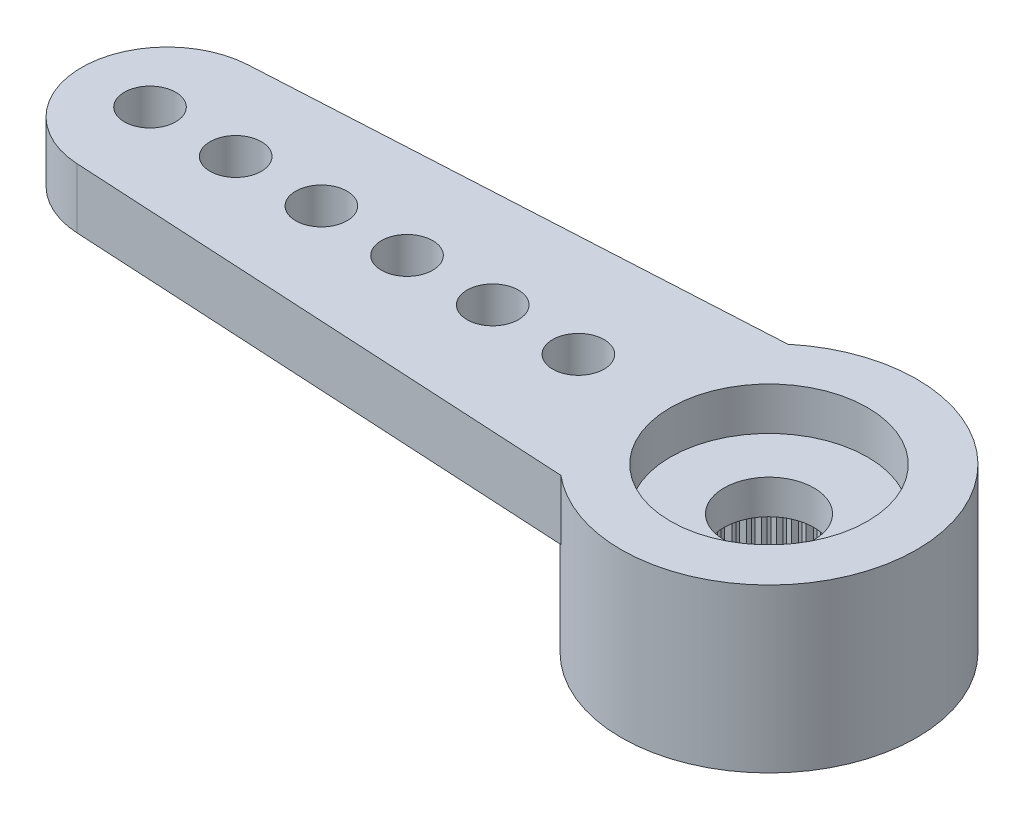
SolidWorks part; units mm, degrees
material "PVC Rígido"
ref_plane "Plano frontal" through (0, 0, 0) normal (0, 0, 1) x (1, 0, 0)
ref_plane "Plano superior" through (0, 0, 0) normal (0, 1, 0) x (1, 0, 0)
ref_plane "Plano direito" through (0, 0, 0) normal (1, 0, 0) x (0, 0, -1)
sketch "Esboço1" plane through (0, 0, 0) normal (0, 1, 0) x (1, 0, 0)
  line L0 (0, 0) -> (-14.05, 0) construction
  line L1 (-14.1591, 1.997) -> (-2.2091, 2.65)
  line L2 (-2.2091, -2.65) -> (-14.1591, -1.997)
  arc A0 (-2.2091, -2.65) -> (-2.2091, 2.65) centre (0, 0) ccw
  arc A1 (-14.1591, 1.997) -> (-14.1591, -1.997) centre (-14.05, 0) ccw
  dimension "D1" = 6.9
  dimension "D2" = 4
  dimension "D3" = 19.5
  dimension "D4" = 5.3
extrude "Ressalto-extrusão1" add sketch "Esboço1" against normal blind 1.4
sketch "Esboço2" plane through (0, -1.4, 0) normal (0, -1, 0) x (1, 0, 0)
  arc A0 (-2.2091, -2.65) -> (-2.2091, 2.65) centre (0, 0) ccw construction
  circle A1 centre (0, 0) radius 3.45
extrude "Ressalto-extrusão2" add sketch "Esboço2" along normal offset from surface (2.4 mm away) 3.8 up to face at (-7.242, 0, 0)
hole_wizard "Furo4" positions "Esboço9" profile "Esboço10" legacy end condition through all
sketch "Esboço9" plane through (0, 0, 0) normal (0, 1, 0) x (1, 0, 0)
  line L1 (-14.45, 0) -> (0, 0) construction
  arc A2 (-14.1591, 1.997) -> (-14.1591, -1.997) centre (-14.05, 0) ccw construction
  point P0 (-14.45, 0)
  point P19 (-16.05, 0)
  dimension "D1" = 1.6
sketch "Esboço10" plane through (-14.45, 0, 0) normal (1, 0, 0) x (0, 0, 1)
  line L0 (0, 0) -> (0, 3.8)
  line L1 (0, 3.8) -> (0.6, 3.8)
  line L2 (0.6, 3.8) -> (0.6, 0)
  line L3 (0.6, 0) -> (0, 0)
  line L4 (0, 110) -> (0, -10) construction
  dimension "Diameter" = 1.2
  dimension "Depth" = 3.8
pattern_linear "Padrão linear1" count 6 spacing 2 along (1, 0, 0) of "Furo4"
hole_wizard "Furo1" positions "Esboço3" profile "Esboço4" legacy
sketch "Esboço3" plane through (0, -3.8, 0) normal (0, -1, 0) x (-1, 0, 0)
  point P0 (0, 0)
sketch "Esboço4" plane through (0, -3.8, 0) normal (1, 0, 0) x (0, 0, -1)
  line L0 (0, 0) -> (0, 2)
  line L1 (0, 2) -> (2.475, 2)
  line L2 (2.475, 2) -> (2.475, 0)
  line L3 (2.475, 0) -> (0, 0)
  line L4 (0, 110) -> (0, -10) construction
  dimension "Diameter" = 4.95
  dimension "Depth" = 2
hole_wizard "Furo2" positions "Esboço5" profile "Esboço6" legacy
sketch "Esboço5" plane through (0, 0, 0) normal (0, 1, 0) x (1, 0, 0)
  point P0 (0, 0)
sketch "Esboço6" plane through (0, 0, 0) normal (1, 0, 0) x (0, 0, 1)
  line L0 (0, 0) -> (0, 1)
  line L1 (0, 1) -> (2.3, 1)
  line L2 (2.3, 1) -> (2.3, 0)
  line L3 (2.3, 0) -> (0, 0)
  line L4 (0, 110) -> (0, -10) construction
  dimension "Diameter" = 4.6
  dimension "Depth" = 1
hole_wizard "Furo3" positions "Esboço7" profile "Esboço8" legacy end condition through all
sketch "Esboço7" plane through (0, 0, 0) normal (0, 1, 0) x (1, 0, 0)
  point P0 (0, 0)
sketch "Esboço8" plane through (0, 0, 0) normal (1, 0, 0) x (0, 0, 1)
  line L0 (0, 0) -> (0, 3.8)
  line L1 (0, 3.8) -> (1.05, 3.8)
  line L2 (1.05, 3.8) -> (1.05, 0)
  line L3 (1.05, 0) -> (0, 0)
  line L4 (0, 110) -> (0, -10) construction
  dimension "Diameter" = 2.1
  dimension "Depth" = 3.8
sketch "Esboço11" plane through (0, -3.8, 0) normal (0, -1, 0) x (1, 0, 0)
  line L0 (-0.0981, 2.4731) -> (0, 2.375)
  line L1 (0, 2.375) -> (0.0981, 2.4731)
  line L2 (0, 0) -> (0, 2.475) construction
  circle A0 centre (0, 0) radius 2.375 construction
  circle A1 centre (0, 0) radius 2.475
  arc A2 (0.0981, 2.4731) -> (-0.0981, 2.4731) centre (0, 0) ccw
  dimension "D3" = 4.75
  dimension "D2" = 0.1
  dimension "D1" = 0
extrude "Ressalto-extrusão3" add sketch "Esboço11" against normal up to surface (2 mm away) up to face at (0, -1.8, 1.05)
pattern_circular "PadrãoCircular1" count 60 over 360 about axis through (0, 0, 0) along (0, 1, 0) of "Ressalto-extrusão3"
sketch "Sketch1" plane through (0, 0, 0) normal (0, 1, 0) x (1, 0, 0)
  line L0 (0, 0) -> (-4.45, 0) construction
  line L1 (0, 0) -> (0, 3.45) construction
  arc A0 (-2.2091, -2.65) -> (-2.2091, 2.65) centre (0, 0) ccw construction
sketch "Sketch2" plane through (0, 0, 0) normal (0, 0, 1) x (1, 0, 0)
  line L0 (0, 0) -> (0, -3.7861) construction
ref_point "Point2"
